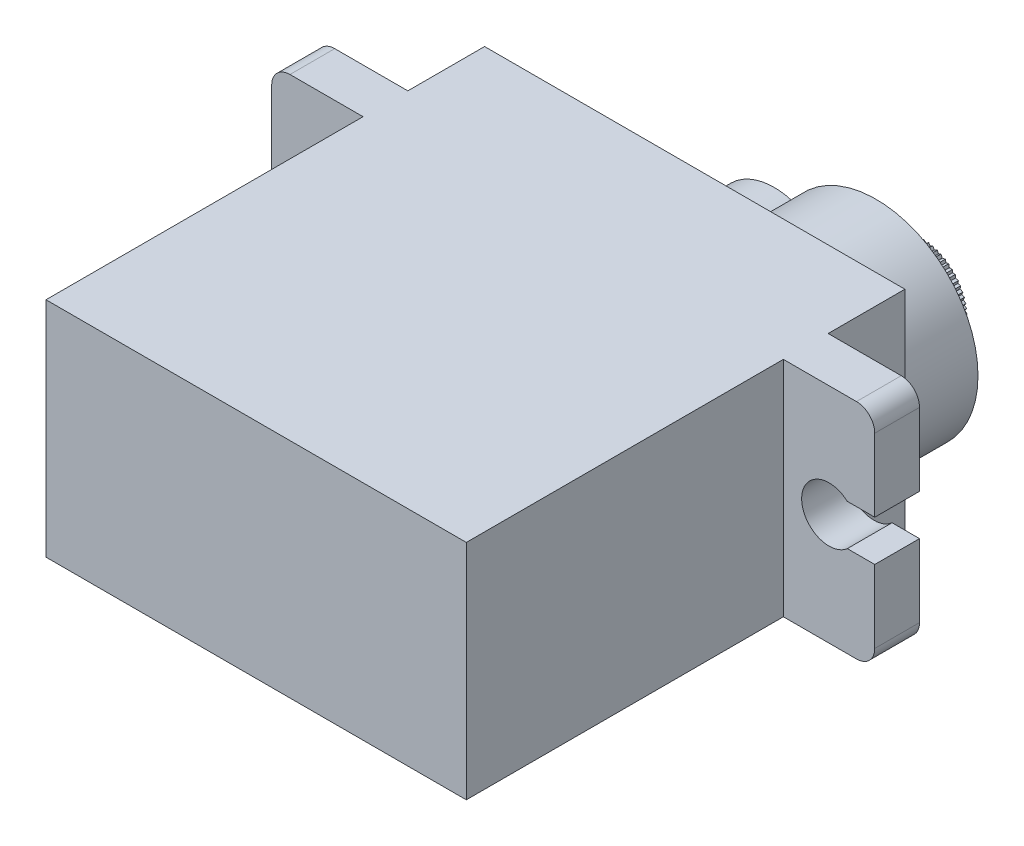
SolidWorks part; units mm, degrees
other "İşaretleme1"
sketch "Çizim23" plane through (16.5, -6.05, -13.15) normal (0.0047, -0.3236, -0.9462) x (-0.9915, -0.1242, 0.0376)
ref_plane "Ön Düzlem" through (0, 0, 0) normal (0, 0, 1) x (1, 0, 0)
ref_plane "Üst Düzlem" through (0, 0, 0) normal (0, 1, 0) x (1, 0, 0)
ref_plane "Sağ Düzlem" through (0, 0, 0) normal (1, 0, 0) x (0, 0, -1)
sketch "Çizim1" plane through (0, 0, 0) normal (0, 0, 1) x (1, 0, 0)
  line L1 (-11.5, -6.1) -> (11.5, -6.1)
  line L2 (-11.5, -6.1) -> (-11.5, 6.1)
  line L3 (-11.5, 6.1) -> (11.5, 6.1)
  line L4 (11.5, -6.1) -> (11.5, 6.1)
  line L5 (-11.5, -6.1) -> (11.5, 6.1) construction
  line L6 (-11.5, 6.1) -> (11.5, -6.1) construction
  point P0 (0, 0)
  dimension "D1" = 23
  dimension "D2" = 12.2
extrude "Yükseklik-Ekstrüzyon1" add sketch "Çizim1" along normal blind 17.35
sketch "Çizim4" plane through (11.5, 0, 0) normal (1, 0, 0) x (0, 0, -1)
  line L0 (-17.35, -6.1) -> (0, -6.1) construction
  line L1 (0, 6.1) -> (2.45, 6.1)
  line L2 (0, 6.1) -> (0, -6.1)
  line L3 (0, -6.1) -> (2.45, -6.1)
  line L4 (2.45, 6.1) -> (2.45, -6.1)
  dimension "D1" = 2.45
extrude "Yükseklik-Ekstrüzyon2" add sketch "Çizim4" along normal blind 5
sketch "Çizim5" plane through (-11.5, 0, 0) normal (-1, 0, 0) x (0, 0, 1)
  line L0 (17.35, 6.1) -> (0, 6.1) construction
  line L1 (0, -6.1) -> (-2.45, -6.1)
  line L2 (0, -6.1) -> (0, 6.1)
  line L3 (0, 6.1) -> (-2.45, 6.1)
  line L4 (-2.45, -6.1) -> (-2.45, 6.1)
  dimension "D1" = 2.45
extrude "Yükseklik-Ekstrüzyon3" add sketch "Çizim5" along normal blind 5
sketch "Çizim6" plane through (16.5, 0, 0) normal (1, 0, 0) x (0, 0, -1)
  line L0 (0, 0) -> (2.45, 0) construction
  line L1 (0, 6.1) -> (0, -6.1) construction
  line L2 (2.45, -6.1) -> (2.45, 6.1) construction
  line L4 (2.45, 1.12) -> (0, 1.12)
  line L5 (2.45, 1.12) -> (2.45, -1.12)
  line L6 (2.45, -1.12) -> (0, -1.12)
  line L7 (0, 1.12) -> (0, -1.12)
  line L8 (2.45, 1.12) -> (0, -1.12) construction
  line L9 (2.45, -1.12) -> (0, 1.12) construction
  point P6 (1.225, 0)
  dimension "D1" = 2.24
sketch "Çizim7" plane through (0, 0, 0) normal (0, 0, -1) x (-1, 0, 0)
  line L0 (-11.5, 6.1) -> (11.5, 6.1) construction
  line L1 (-11.5, -6.1) -> (11.5, -6.1)
  line L2 (-11.5, -6.1) -> (-11.5, 6.1)
  line L3 (-11.5, 6.1) -> (11.5, 6.1)
  line L4 (11.5, -6.1) -> (11.5, 6.1)
  line L5 (-11.5, -6.1) -> (11.5, 6.1) construction
  line L6 (-11.5, 6.1) -> (11.5, -6.1) construction
  point P0 (0, 0)
  dimension "D1" = 23
extrude "Yükseklik-Ekstrüzyon4" add sketch "Çizim7" along normal blind 6.65
sketch "Çizim8" plane through (0, 0, -2.45) normal (0, 0, -1) x (-1, 0, 0)
  line L0 (0, 0.2404) -> (0, 3.5063) construction
  circle A0 centre (-14, 0) radius 1.5
  circle A1 centre (14, 0) radius 1.5
  dimension "D2" = 3
  dimension "D1" = 2.5
extrude "Kes-Ekstrüzyon1" cut sketch "Çizim8" against normal up to surface (2.45 mm away) up to face at (14, 0, 0)
fillet "Radyus1" radius 1 4 edges at (-16.5, 6.1, -1.225) (-16.5, -6.1, -1.225) (16.5, -6.1, -1.225) (16.5, 6.1, -1.225)
extrude "Kes-Ekstrüzyon2" cut sketch "Çizim6" against normal up to surface (1.5022 mm away)
sketch "Çizim9" plane through (-16.5, 0, 0) normal (-1, 0, 0) x (0, 0, 1)
  line L0 (0, 0) -> (-2.45, 0) construction
  line L1 (-2.45, 6.1) -> (-2.45, -6.1) construction
  line L2 (0, -6.1) -> (0, 6.1) construction
  line L3 (-2.45, -1.12) -> (0, -1.12)
  line L4 (-2.45, -1.12) -> (-2.45, 1.12)
  line L5 (-2.45, 1.12) -> (0, 1.12)
  line L6 (0, -1.12) -> (0, 1.12)
  line L7 (-2.45, -1.12) -> (0, 1.12) construction
  line L8 (-2.45, 1.12) -> (0, -1.12) construction
  point P5 (-1.225, 0)
  dimension "D1" = 2.24
extrude "Kes-Ekstrüzyon3" cut sketch "Çizim9" against normal up to surface (1.5022 mm away)
sketch "Çizim10" plane through (0, 0, -6.65) normal (0, 0, -1) x (-1, 0, 0)
  line L0 (-11.5, 0) -> (-5.925, 0) construction
  line L1 (-11.5, 6.1) -> (-11.5, -6.1) construction
  circle A0 centre (-5.925, 0) radius 5.575
  dimension "D2" = 11.15
  dimension "D1" = 5.575
extrude "Yükseklik-Ekstrüzyon5" add sketch "Çizim10" along normal blind 4
sketch "Çizim11" plane through (0, 0, -10.65) normal (0, 0, -1) x (-1, 0, 0)
  circle A0 centre (-5.925, 0) radius 2.5
  dimension "D1" = 5
extrude "Yükseklik-Ekstrüzyon6" add sketch "Çizim11" along normal blind 2.5
sketch "Çizim12" plane through (0, 0, -6.65) normal (0, 0, -1) x (-1, 0, 0)
  line L0 (-0.35, 0) -> (3, 0) construction
  circle A0 centre (-5.925, 0) radius 5.575 construction
  circle A1 centre (-5.925, 0) radius 5.575 construction
  circle A2 centre (-0.35, 0) radius 3.35
  dimension "D1" = 3.35
extrude "Yükseklik-Ekstrüzyon7" add sketch "Çizim12" along normal blind 4
sketch "Çizim13" plane through (0, 0, -13.15) normal (0, 0, -1) x (-1, 0, 0)
  line L0 (-5.925, 2.375) -> (-5.815, 2.485)
  line L1 (-5.925, 2.375) -> (-6.035, 2.485)
  line L2 (-6.035, 2.485) -> (-6.1562, 2.3637)
  line L3 (-5.815, 2.485) -> (-5.6938, 2.3637)
  line L4 (-5.5481, 2.4587) -> (-5.6906, 2.3634)
  line L5 (-5.4617, 2.3294) -> (-5.5481, 2.4587)
  line L6 (-5.4617, 2.3294) -> (-5.3324, 2.4158)
  line L7 (-5.3324, 2.4158) -> (-5.2371, 2.2732)
  line L8 (-5.0756, 2.3379) -> (-5.234, 2.2723)
  line L9 (-5.0161, 2.1942) -> (-5.0756, 2.3379)
  line L10 (-5.0161, 2.1942) -> (-4.8725, 2.2537)
  line L11 (-4.8725, 2.2537) -> (-4.8068, 2.0953)
  line L12 (-4.6359, 2.1273) -> (-4.804, 2.0938)
  line L13 (-4.6055, 1.9747) -> (-4.6359, 2.1273)
  line L14 (-4.6055, 1.9747) -> (-4.453, 2.0051)
  line L15 (-4.453, 2.0051) -> (-4.4196, 1.8369)
  line L16 (-4.2456, 1.8349) -> (-4.4171, 1.8349)
  line L17 (-4.2456, 1.6794) -> (-4.2456, 1.8349)
  line L18 (-4.2456, 1.6794) -> (-4.0901, 1.6794)
  line L19 (-4.0901, 1.6794) -> (-4.0901, 1.5079)
  line L20 (-3.9199, 1.472) -> (-4.0881, 1.5054)
  line L21 (-3.9503, 1.3195) -> (-3.9199, 1.472)
  line L22 (-3.9503, 1.3195) -> (-3.7977, 1.2891)
  line L23 (-3.7977, 1.2891) -> (-3.8312, 1.121)
  line L24 (-3.6713, 1.0525) -> (-3.8297, 1.1182)
  line L25 (-3.7308, 0.9089) -> (-3.6713, 1.0525)
  line L26 (-3.7308, 0.9089) -> (-3.5871, 0.8494)
  line L27 (-3.5871, 0.8494) -> (-3.6527, 0.691)
  line L28 (-3.5092, 0.5926) -> (-3.6518, 0.6879)
  line L29 (-3.5956, 0.4633) -> (-3.5092, 0.5926)
  line L30 (-3.5956, 0.4633) -> (-3.4663, 0.3769)
  line L31 (-3.4663, 0.3769) -> (-3.5616, 0.2344)
  line L32 (-3.44, 0.11) -> (-3.5613, 0.2312)
  line L33 (-3.55, 0) -> (-3.44, 0.11)
  line L34 (-3.55, 0) -> (-3.44, -0.11)
  line L35 (-3.44, -0.11) -> (-3.5613, -0.2312)
  line L36 (-3.4663, -0.3769) -> (-3.5616, -0.2344)
  line L37 (-3.5956, -0.4633) -> (-3.4663, -0.3769)
  line L38 (-3.5956, -0.4633) -> (-3.5092, -0.5926)
  line L39 (-3.5092, -0.5926) -> (-3.6518, -0.6879)
  line L40 (-3.5871, -0.8494) -> (-3.6527, -0.691)
  line L41 (-3.7308, -0.9089) -> (-3.5871, -0.8494)
  line L42 (-3.7308, -0.9089) -> (-3.6713, -1.0525)
  line L43 (-3.6713, -1.0525) -> (-3.8297, -1.1182)
  line L44 (-3.7977, -1.2891) -> (-3.8312, -1.121)
  line L45 (-3.9503, -1.3195) -> (-3.7977, -1.2891)
  line L46 (-3.9503, -1.3195) -> (-3.9199, -1.472)
  line L47 (-3.9199, -1.472) -> (-4.0881, -1.5054)
  line L48 (-4.0901, -1.6794) -> (-4.0901, -1.5079)
  line L49 (-4.2456, -1.6794) -> (-4.0901, -1.6794)
  line L50 (-4.2456, -1.6794) -> (-4.2456, -1.8349)
  line L51 (-4.2456, -1.8349) -> (-4.4171, -1.8349)
  line L52 (-4.453, -2.0051) -> (-4.4196, -1.8369)
  line L53 (-4.6055, -1.9747) -> (-4.453, -2.0051)
  line L54 (-4.6055, -1.9747) -> (-4.6359, -2.1273)
  line L55 (-4.6359, -2.1273) -> (-4.804, -2.0938)
  line L56 (-4.8725, -2.2537) -> (-4.8068, -2.0953)
  line L57 (-5.0161, -2.1942) -> (-4.8725, -2.2537)
  line L58 (-5.0161, -2.1942) -> (-5.0756, -2.3379)
  line L59 (-5.0756, -2.3379) -> (-5.234, -2.2723)
  line L60 (-5.3324, -2.4158) -> (-5.2371, -2.2732)
  line L61 (-5.4617, -2.3294) -> (-5.3324, -2.4158)
  line L62 (-5.4617, -2.3294) -> (-5.5481, -2.4587)
  line L63 (-5.5481, -2.4587) -> (-5.6906, -2.3634)
  line L64 (-5.815, -2.485) -> (-5.6938, -2.3637)
  line L65 (-5.925, -2.375) -> (-5.815, -2.485)
  line L66 (-5.925, -2.375) -> (-6.035, -2.485)
  line L67 (-6.035, -2.485) -> (-6.1562, -2.3637)
  line L68 (-6.3019, -2.4587) -> (-6.1594, -2.3634)
  line L69 (-6.3883, -2.3294) -> (-6.3019, -2.4587)
  line L70 (-6.3883, -2.3294) -> (-6.5176, -2.4158)
  line L71 (-6.5176, -2.4158) -> (-6.6129, -2.2732)
  line L72 (-6.7744, -2.3379) -> (-6.616, -2.2723)
  line L73 (-6.8339, -2.1942) -> (-6.7744, -2.3379)
  line L74 (-6.8339, -2.1942) -> (-6.9775, -2.2537)
  line L75 (-6.9775, -2.2537) -> (-7.0432, -2.0953)
  line L76 (-7.2141, -2.1273) -> (-7.046, -2.0938)
  line L77 (-7.2445, -1.9747) -> (-7.2141, -2.1273)
  line L78 (-7.2445, -1.9747) -> (-7.397, -2.0051)
  line L79 (-7.397, -2.0051) -> (-7.4304, -1.8369)
  line L80 (-7.6044, -1.8349) -> (-7.4329, -1.8349)
  line L81 (-7.6044, -1.6794) -> (-7.6044, -1.8349)
  line L82 (-7.6044, -1.6794) -> (-7.7599, -1.6794)
  line L83 (-7.7599, -1.6794) -> (-7.7599, -1.5079)
  line L84 (-7.9301, -1.472) -> (-7.7619, -1.5054)
  line L85 (-7.8997, -1.3195) -> (-7.9301, -1.472)
  line L86 (-7.8997, -1.3195) -> (-8.0523, -1.2891)
  line L87 (-8.0523, -1.2891) -> (-8.0188, -1.121)
  line L88 (-8.1787, -1.0525) -> (-8.0203, -1.1182)
  line L89 (-8.1192, -0.9089) -> (-8.1787, -1.0525)
  line L90 (-8.1192, -0.9089) -> (-8.2629, -0.8494)
  line L91 (-8.2629, -0.8494) -> (-8.1973, -0.691)
  line L92 (-8.3408, -0.5926) -> (-8.1982, -0.6879)
  line L93 (-8.2544, -0.4633) -> (-8.3408, -0.5926)
  line L94 (-8.2544, -0.4633) -> (-8.3837, -0.3769)
  line L95 (-8.3837, -0.3769) -> (-8.2884, -0.2344)
  line L96 (-8.41, -0.11) -> (-8.2887, -0.2312)
  line L97 (-8.3, 0) -> (-8.41, -0.11)
  line L98 (-8.3, 0) -> (-8.41, 0.11)
  line L99 (-8.41, 0.11) -> (-8.2887, 0.2312)
  line L100 (-8.3837, 0.3769) -> (-8.2884, 0.2344)
  line L101 (-8.2544, 0.4633) -> (-8.3837, 0.3769)
  line L102 (-8.2544, 0.4633) -> (-8.3408, 0.5926)
  line L103 (-8.3408, 0.5926) -> (-8.1982, 0.6879)
  line L104 (-8.2629, 0.8494) -> (-8.1973, 0.691)
  line L105 (-8.1192, 0.9089) -> (-8.2629, 0.8494)
  line L106 (-8.1192, 0.9089) -> (-8.1787, 1.0525)
  line L107 (-8.1787, 1.0525) -> (-8.0203, 1.1182)
  line L108 (-8.0523, 1.2891) -> (-8.0188, 1.121)
  line L109 (-7.8997, 1.3195) -> (-8.0523, 1.2891)
  line L110 (-7.8997, 1.3195) -> (-7.9301, 1.472)
  line L111 (-7.9301, 1.472) -> (-7.7619, 1.5054)
  line L112 (-7.7599, 1.6794) -> (-7.7599, 1.5079)
  line L113 (-7.6044, 1.6794) -> (-7.7599, 1.6794)
  line L114 (-7.6044, 1.6794) -> (-7.6044, 1.8349)
  line L115 (-7.6044, 1.8349) -> (-7.4329, 1.8349)
  line L116 (-7.397, 2.0051) -> (-7.4304, 1.8369)
  line L117 (-7.2445, 1.9747) -> (-7.397, 2.0051)
  line L118 (-7.2445, 1.9747) -> (-7.2141, 2.1273)
  line L119 (-7.2141, 2.1273) -> (-7.046, 2.0938)
  line L120 (-6.9775, 2.2537) -> (-7.0432, 2.0953)
  line L121 (-6.8339, 2.1942) -> (-6.9775, 2.2537)
  line L122 (-6.8339, 2.1942) -> (-6.7744, 2.3379)
  line L123 (-6.7744, 2.3379) -> (-6.616, 2.2723)
  line L124 (-6.5176, 2.4158) -> (-6.6129, 2.2732)
  line L125 (-6.3883, 2.3294) -> (-6.5176, 2.4158)
  line L126 (-6.3883, 2.3294) -> (-6.3019, 2.4587)
  line L127 (-6.3019, 2.4587) -> (-6.1594, 2.3634)
  line L128 (-8.1973, 0.691) -> (-8.1982, 0.6879)
  line L129 (-8.0188, 1.121) -> (-8.0203, 1.1182)
  line L130 (-7.7599, 1.5079) -> (-7.7619, 1.5054)
  line L131 (-7.4304, 1.8369) -> (-7.4329, 1.8349)
  line L132 (-7.0432, 2.0953) -> (-7.046, 2.0938)
  line L133 (-6.6129, 2.2732) -> (-6.616, 2.2723)
  line L134 (-6.1562, 2.3637) -> (-6.1594, 2.3634)
  line L135 (-5.6906, 2.3634) -> (-5.6938, 2.3637)
  line L136 (-5.234, 2.2723) -> (-5.2371, 2.2732)
  line L137 (-4.804, 2.0938) -> (-4.8068, 2.0953)
  line L138 (-4.4171, 1.8349) -> (-4.4196, 1.8369)
  line L139 (-4.0881, 1.5054) -> (-4.0901, 1.5079)
  line L140 (-3.8297, 1.1182) -> (-3.8312, 1.121)
  line L141 (-3.6518, 0.6879) -> (-3.6527, 0.691)
  line L142 (-3.5613, 0.2312) -> (-3.5616, 0.2344)
  line L143 (-3.5616, -0.2344) -> (-3.5613, -0.2312)
  line L144 (-3.6527, -0.691) -> (-3.6518, -0.6879)
  line L145 (-3.8312, -1.121) -> (-3.8297, -1.1182)
  line L146 (-4.0901, -1.5079) -> (-4.0881, -1.5054)
  line L147 (-4.4196, -1.8369) -> (-4.4171, -1.8349)
  line L148 (-4.8068, -2.0953) -> (-4.804, -2.0938)
  line L149 (-5.2371, -2.2732) -> (-5.234, -2.2723)
  line L150 (-5.6938, -2.3637) -> (-5.6906, -2.3634)
  line L151 (-6.1594, -2.3634) -> (-6.1562, -2.3637)
  line L152 (-6.616, -2.2723) -> (-6.6129, -2.2732)
  line L153 (-7.046, -2.0938) -> (-7.0432, -2.0953)
  line L154 (-7.4329, -1.8349) -> (-7.4304, -1.8369)
  line L155 (-7.7619, -1.5054) -> (-7.7599, -1.5079)
  line L156 (-8.0203, -1.1182) -> (-8.0188, -1.121)
  line L157 (-8.1982, -0.6879) -> (-8.1973, -0.691)
  line L158 (-8.2887, -0.2312) -> (-8.2884, -0.2344)
  line L159 (-8.2884, 0.2344) -> (-8.2887, 0.2312)
  circle A1 centre (-5.925, 0) radius 2.5
  point P167 (-5.925, 0)
  point P229 (-5.925, 0)
  dimension "D1" = 32
  dimension "D2" = 32
extrude "Kes-Ekstrüzyon4" cut sketch "Çizim13" against normal up to surface (2.5 mm away) up to face at (3.425, 0, -10.65)
sketch "Çizim14" plane through (0, 0, -13.15) normal (0, 0, -1) x (-1, 0, 0)
  line L0 (-11.5, 0) -> (-5.925, 0) construction
  line L1 (-11.5, -6.1) -> (-11.5, 6.1) construction
  circle A0 centre (-5.925, 0) radius 0.75
  dimension "D1" = 1.5
extrude "Kes-Ekstrüzyon5" cut sketch "Çizim14" against normal blind 1
sketch "Çizim15" plane through (0, -6.1, 0) normal (0, -1, 0) x (1, 0, 0)
  line L0 (0, 17.35) -> (0, 15.35) construction
  line L1 (-11.5, 17.35) -> (11.5, 17.35) construction
  line L2 (-11.5, 8.675) -> (-9.5, 8.675) construction
  line L3 (-11.5, 17.35) -> (-11.5, 0) construction
  line L4 (11.5, 17.35) -> (11.5, 0) construction
  line L5 (-9.5, 15.35) -> (9.5, 15.35)
  line L6 (-9.5, 15.35) -> (-9.5, 2)
  line L7 (-9.5, 2) -> (9.5, 2)
  line L8 (9.5, 15.35) -> (9.5, 2)
  dimension "D1" = 2
  dimension "D2" = 2
  dimension "D3" = 2
  dimension "D4" = 2
  dimension "D5" = 2
extrude "Yükseklik-Ekstrüzyon8" add sketch "Çizim15" along normal blind 0.1
sketch "Çizim17" plane through (0, -6.2, 0) normal (0, -1, 0) x (1, 0, 0)
  line L0 (-9.5, 8.675) -> (9.5, 8.675) construction
  line L1 (-9.5, 15.35) -> (-9.5, 2) construction
  line L2 (9.5, 2) -> (9.5, 15.35) construction
  line L4 (-9.5, 6.925) -> (9.5, 6.925)
  line L5 (-9.5, 6.925) -> (-9.5, 10.425)
  line L6 (-9.5, 10.425) -> (9.5, 10.425)
  line L7 (9.5, 6.925) -> (9.5, 10.425)
  line L8 (-9.5, 6.925) -> (9.5, 10.425) construction
  line L9 (-9.5, 10.425) -> (9.5, 6.925) construction
  point P6 (0, 8.675)
  dimension "D1" = 3.5
extrude "Yükseklik-Ekstrüzyon9" add sketch "Çizim17" along normal blind 0.05
sketch "Çizim18" plane through (0, -6.25, 0) normal (0, -1, 0) x (1, 0, 0)
  line L0 (-9.5, 9.425) -> (9.5, 9.425) construction
  line L2 (9.5, 6.925) -> (9.5, 10.425) construction
  line L3 (9.5, 9.425) -> (9.5, 10.425) construction
  line L4 (9.5, 2) -> (9.5, 15.35) construction
  line L7 (-9.5, 15.35) -> (-9.5, 2) construction
  text T0 "MG90S" font "Century Gothic" height 1.5
extrude "Kes-Ekstrüzyon7" cut sketch "Çizim18" against normal blind 0.05
sketch "Çizim19" plane through (0, -6.2, 0) normal (0, -1, 0) x (1, 0, 0)
  line L0 (9.5, 12.8875) -> (-9.5, 12.8875) construction
  line L1 (9.5, 10.425) -> (9.5, 15.35) construction
  line L2 (-9.5, 15.35) -> (-9.5, 10.425) construction
  text T0 "MİCRO SERVO" font "Century Gothic" height 1.5
extrude "Kes-Ekstrüzyon8" cut sketch "Çizim19" against normal blind 0.1
sketch "Çizim21" plane through (0, -6.1, 0) normal (0, -1, 0) x (1, 0, 0)
  line L11 (-9.5, 2) -> (9.5, 2) construction
  line L12 (9.5, 2) -> (9.5, 15.35) construction
  line L13 (-9.5, 15.35) -> (-9.5, 2) construction
  line L14 (9.5, 15.35) -> (-9.5, 15.35) construction
  line L15 (-9.75, 1.75) -> (9.75, 1.75)
  line L16 (9.75, 1.75) -> (9.75, 15.6)
  line L17 (-9.75, 15.6) -> (-9.75, 1.75)
  line L18 (9.75, 15.6) -> (-9.75, 15.6)
  line L19 (-9.75, 1.75) -> (9.75, 1.75)
  line L20 (9.75, 1.75) -> (9.75, 15.6)
  line L21 (-9.75, 15.6) -> (-9.75, 1.75)
  line L22 (9.75, 15.6) -> (-9.75, 15.6)
  line L23 (-9.5, 2) -> (9.5, 2)
  line L24 (9.5, 2) -> (9.5, 15.35)
  line L25 (-9.5, 15.35) -> (-9.5, 2)
  line L26 (9.5, 15.35) -> (-9.5, 15.35)
  dimension "D1" = 0.25
extrude "Yükseklik-Ekstrüzyon10" add sketch "Çizim21" along normal blind 0.11
sketch "Çizim22" plane through (0, -6.1, 0) normal (0, -1, 0) x (1, 0, 0)
  line L0 (-9.75, 1.75) -> (9.75, 1.75) construction
  line L1 (9.75, 1.75) -> (9.75, 15.6) construction
  line L2 (9.75, 15.6) -> (-9.75, 15.6) construction
  line L3 (-9.75, 15.6) -> (-9.75, 1.75) construction
  line L4 (-9.75, 1.75) -> (9.75, 1.75)
  line L5 (9.75, 1.75) -> (9.75, 15.6)
  line L6 (9.75, 15.6) -> (-9.75, 15.6)
  line L7 (-9.75, 15.6) -> (-9.75, 1.75)
  line L8 (10, 15.85) -> (-10, 15.85)
  line L9 (-10, 15.85) -> (-10, 1.5)
  line L10 (-10, 1.5) -> (10, 1.5)
  line L11 (10, 1.5) -> (10, 15.85)
  dimension "D1" = 0.25
extrude "Yükseklik-Ekstrüzyon11" add sketch "Çizim22" along normal blind 0.1
sketch "Esquisse3" plane through (0, 6.1, 0) normal (0, 1, 0) x (1, 0, 0)
  line L0 (11.5, 2.45) -> (11.5, -17.35)
